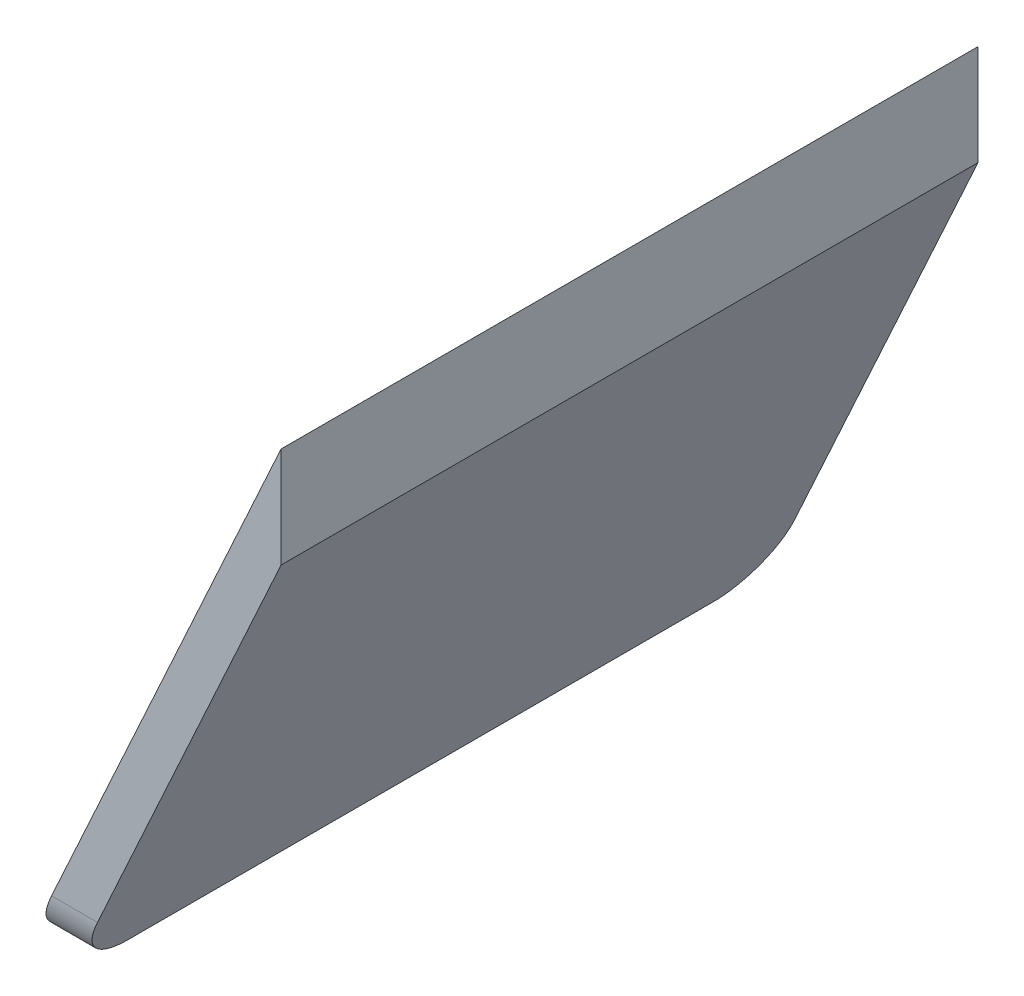
SolidWorks part; units mm, degrees
ref_plane "Front Plane" through (0, 0, 0) normal (0, 0, 1) x (1, 0, 0)
ref_plane "Top Plane" through (0, 0, 0) normal (0, 1, 0) x (1, 0, 0)
ref_plane "Right Plane" through (0, 0, 0) normal (1, 0, 0) x (0, 0, -1)
sketch "Sketch1" plane through (0, 0, 0) normal (0, 0, 1) x (1, 0, 0)
  line L0 (0, 0) -> (15, 32.7886)
  line L1 (15, 32.7886) -> (15, 40)
  line L2 (15, 40) -> (-3.299, 0)
  line L3 (-3.299, 0) -> (0, 0)
  dimension "D1" = 3
  dimension "D2" = 15
  dimension "D3" = 40
extrude "Boss-Extrude1" add sketch "Sketch1" along normal blind 50
fillet "Fillet1" radius 4 2 edges at (-1.6495, 0, 0) (-1.6495, 0, 50)
sketch "Sketch2" plane through (-2.7281, 1.248, 0) normal (-0.9094, 0.416, 0) x (0, 0, 1)
  line L1 (20, 12.8204) -> (30, 12.8204)
  line L2 (26, 26.8204) -> (26, 32.8204)
  line L20 (22, 18.8204) -> (28, 18.8204)
  line L21 (22, 18.8204) -> (22, 26.8204)
  line L22 (28, 18.8204) -> (28, 26.8204)
  line L23 (22, 26.8204) -> (24, 26.8204)
  line L24 (24, 26.8204) -> (24, 32.8204)
  line L25 (24, 32.8204) -> (13.5, 32.8204)
  line L26 (13.5, 32.8204) -> (13.5, 26.8204)
  line L27 (13.5, 26.8204) -> (15.5, 26.8204)
  line L28 (15.5, 26.8204) -> (15.5, 16.8204)
  line L29 (28, 26.8204) -> (26, 26.8204)
  line L30 (26, 32.8204) -> (36.5, 32.8204)
  line L31 (36.5, 32.8204) -> (36.5, 26.8204)
  line L32 (36.5, 26.8204) -> (34.5, 26.8204)
  line L33 (34.5, 26.8204) -> (34.5, 16.8204)
  line L34 (15.5, 16.8204) -> (20, 12.8204)
  line L35 (30, 12.8204) -> (34.5, 16.8204)
  line L36 (50, 42.6146) -> (50, 3.0263) construction
  line L37 (22, 22.8204) -> (28, 22.8204) construction
  line L39 (50, 42.6146) -> (0, 42.6146) construction
  point P4 (25, 18.8204)
  point P5 (25, 12.8204)
  point P24 (25, 42.6146)
  point P25 (25, 22.8204)
  point P28 (50, 22.8204)
  dimension "D1" = 10
  dimension "D2" = 6
  dimension "D3" = 8
  dimension "D4" = 2
  dimension "D5" = 6
  dimension "D6" = 2
  dimension "D7" = 6.5
  dimension "D8" = 2
  dimension "D9" = 2
  dimension "D10" = 6.5
  dimension "D11" = 10
  dimension "D12" = 10
  dimension "D13" = 6
  dimension "D15" = 20
  dimension "D17" = 6
  dimension "D18" = 10.5
  dimension "D19" = 10.5
extrude "Cut-Extrude1" cut sketch "Sketch2" against normal blind 1.5 contours L25 L26 L27 L28 L34 L1 L35 L33 L32 L31 L30 L2 L29 L22 L20 L21 L23 L24
